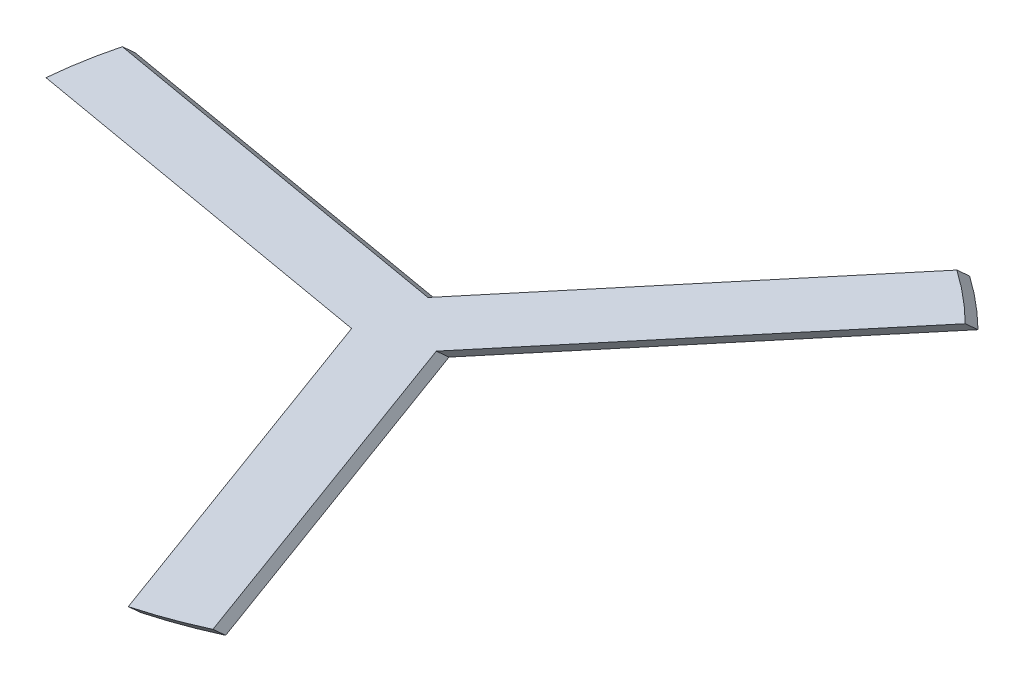
SolidWorks part; units mm, degrees
ref_plane "Front Plane" through (0, 0, 0) normal (0, 0, 1) x (1, 0, 0)
ref_plane "Top Plane" through (0, 0, 0) normal (0, 1, 0) x (1, 0, 0)
ref_plane "Right Plane" through (0, 0, 0) normal (1, 0, 0) x (0, 0, -1)
sketch "Sketch2" plane through (0, 0, 0) normal (0, 1, 0) x (1, 0, 0)
  line L0 (-2735.8251, -3682.8801) -> (-2725.3147, -3670.9459)
  line L3 (-3307.6698, -3179.2555) -> (-3297.1593, -3167.3213)
  line L4 (-2735.8251, -3682.8801) -> (-2726.3749, -3670.1585) construction
  line L6 (-1821.5552, 4210.7341) -> (-1816.4751, 4195.6647)
  line L7 (-1099.4812, 4454.1538) -> (-1094.4011, 4439.0844)
  line L8 (4557.3803, -527.854) -> (4541.7898, -524.7188)
  line L9 (4407.1509, -1274.8983) -> (4391.5604, -1271.763)
  line L10 (-281.198, -332.0791) -> (-4541.7898, 524.7188)
  line L11 (-3296.2443, -3168.2736) -> (-3307.6698, -3179.2555) construction
  line L13 (431.3062, -86.735) -> (3297.1593, 3167.3213)
  line L14 (-290.7678, -330.1547) -> (1094.4011, -4439.0844)
  line L16 (431.3062, -86.735) -> (1816.4751, -4195.6647)
  line L18 (-140.5384, 416.8896) -> (-4391.5604, 1271.763)
  line L19 (-140.5384, 416.8896) -> (2725.3147, 3670.9459)
  arc A0 (-4391.5604, 1271.763) -> (-4541.7898, 524.7188) centre (0, 0) ccw
  arc A2 (3297.1593, 3167.3213) -> (2725.3147, 3670.9459) centre (0, 0) ccw
  arc A4 (1094.4011, -4439.0844) -> (1816.4751, -4195.6647) centre (0, 0) ccw
  arc A5 (-3297.1593, -3167.3213) -> (-3296.2443, -3168.2736) centre (0, 0) ccw
  arc A6 (-2726.3749, -3670.1585) -> (-2725.3147, -3670.9459) centre (0, 0) ccw
  point P3 (0, 0)
  point P18 (0, 0)
  point P38 (0, 0)
  dimension "D1" = 762
  dimension "D2" = 9144
  dimension "D4" = 3
ref_plane "Plane1" through (0, 101.6, 0) normal (0, 1, 0) x (1, 0, 0)
sketch "Sketch3" plane through (0, 101.6, 0) normal (0, 1, 0) x (1, 0, 0)
  line L0 (-2638.4811, -3753.2336) -> (-2628.2866, -3741.0284)
  line L1 (-2638.4811, -3753.2336) -> (-2930.8971, -3508.9922)
  line L3 (-3223.3131, -3264.7508) -> (-3213.1186, -3252.5456)
  line L4 (-2638.4811, -3753.2336) -> (-2629.3671, -3740.2691) construction
  line L5 (3212.179, 3253.4735) -> (0, 0) construction
  line L6 (-1931.1551, 4161.6084) -> (-1925.6823, 4146.6772)
  line L7 (-1215.7006, 4423.8464) -> (-1210.2278, 4408.9151)
  line L8 (4578.7603, -288.6157) -> (4563.06, -286.0956)
  line L9 (4447.2959, -1160.5367) -> (4431.634, -1157.8116)
  line L10 (-282.0257, -337.6529) -> (1210.2278, -4408.9151)
  line L13 (-3212.179, -3253.4735) -> (-3223.3131, -3264.7508) construction
  line L17 (-282.0257, -337.6529) -> (-4553.9689, 405.6488)
  line L18 (-151.4032, 413.0679) -> (-4423.3464, 1156.3696)
  line L19 (-151.4032, 413.0679) -> (2628.2866, 3741.0284)
  line L21 (0, 0) -> (2629.3671, 3740.2691) construction
  line L22 (433.4289, -75.415) -> (1925.6823, -4146.6772)
  line L23 (433.4289, -75.415) -> (3213.1186, 3252.5456)
  arc A1 (3213.1186, 3252.5456) -> (2628.2866, 3741.0284) centre (0, 0) ccw
  arc A3 (1210.2278, -4408.9151) -> (1925.6823, -4146.6772) centre (0, 0) ccw
  arc A4 (-3213.1186, -3252.5456) -> (-3212.179, -3253.4735) centre (0, 0) ccw
  arc A5 (-4423.3464, 1156.3696) -> (-4553.9689, 405.6488) centre (0, 0) ccw
  arc A6 (-2930.8971, -3508.9922) -> (-2628.2866, -3741.0284) centre (0, 0) ccw
  point P14 (0, 0)
  dimension "D1" = 762
sketch "Sketch7" plane through (0, 0, 0) normal (1, 0, 0) x (0, 0, -1)
  line L0 (0, 0) -> (0, 101.6)
sketch3d "3DSketch1"
  line L0 (-4391.5604, 0, -1271.763) -> (-4423.3464, 101.6, -1156.3696)
  line L1 (-4541.7898, 0, -524.7188) -> (-4553.9689, 101.6, -405.6488)
  line L2 (3297.1593, 0, -3167.3213) -> (3212.179, 101.6, -3253.4735)
  line L3 (2725.3147, 0, -3670.9459) -> (2629.3671, 101.6, -3740.2691)
  line L4 (-140.5384, 0, -416.8896) -> (-151.4032, 101.6, -413.0679)
  line L5 (-281.198, 0, 332.0791) -> (-282.0257, 101.6, 337.6529)
  line L6 (431.3062, 0, 86.735) -> (433.4289, 101.6, 75.415)
  line L7 (1925.6823, 101.6, 4146.6772) -> (1816.4751, 0, 4195.6647)
  line L8 (1094.4011, 0, 4439.0844) -> (1210.2278, 101.6, 4408.9151)
  arc A0 (-4391.5604, 0, -1271.763) -> (-4541.7898, 0, -524.7188) centre (0, 0, 0) ccw construction
  point P5 (0, 4572, 0)
sketch3d "3DSketch2"
  line L0 (-140.5384, 0, -416.8896) -> (-151.4032, 101.6, -413.0679) construction
  line L1 (-140.5384, 0, -416.8896) -> (-4391.5604, 0, -1271.763) construction
  line L2 (-151.4032, 101.6, -413.0679) -> (-4423.3464, 101.6, -1156.3696) construction
  line L3 (-4391.5604, 0, -1271.763) -> (-4423.3464, 101.6, -1156.3696) construction
  line L4 (-140.5384, 0, -416.8896) -> (-151.4032, 101.6, -413.0679)
  line L5 (-140.5384, 0, -416.8896) -> (-4391.5604, 0, -1271.763)
  line L6 (-151.4032, 101.6, -413.0679) -> (-4423.3464, 101.6, -1156.3696)
  line L7 (-4391.5604, 0, -1271.763) -> (-4423.3464, 101.6, -1156.3696)
sweep "Sweep8" add profiles "Sketch3" path "3DSketch1"
